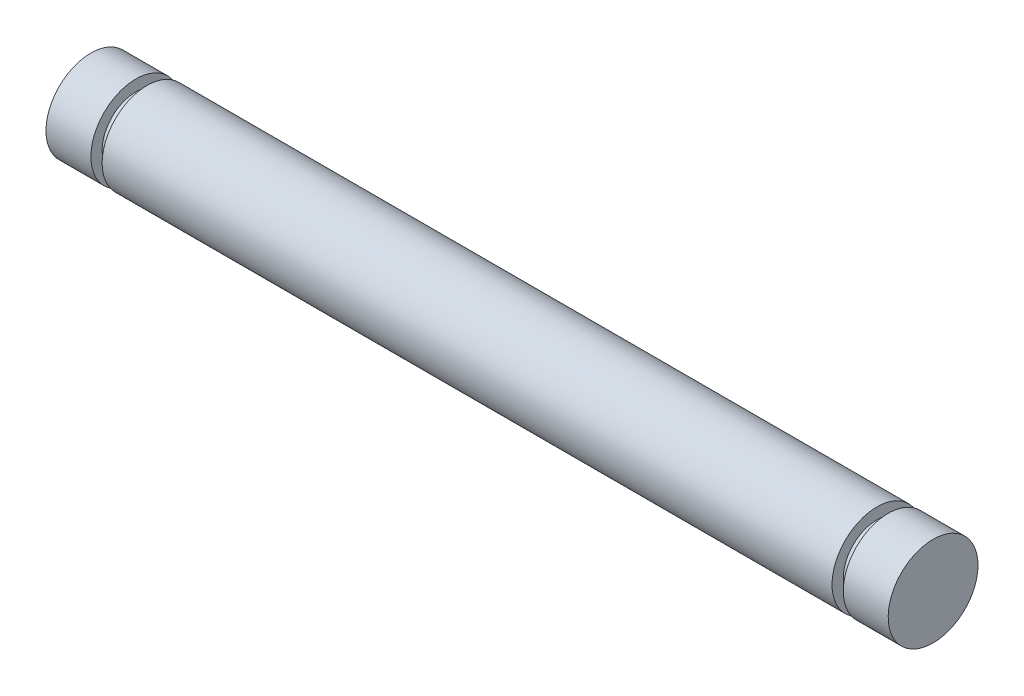
SolidWorks part; units mm, degrees
ref_plane "Alzado" through (0, 0, 0) normal (0, 0, 1) x (1, 0, 0)
ref_plane "Planta" through (0, 0, 0) normal (0, 1, 0) x (1, 0, 0)
ref_plane "Vista lateral" through (0, 0, 0) normal (1, 0, 0) x (0, 0, -1)
sketch "Croquis1" plane through (0, 0, 0) normal (0, 0, 1) x (1, 0, 0)
  line L0 (-37.5, 0) -> (37.5, 0) construction
  line L1 (-37.5, 0) -> (-37.5, 4)
  line L2 (-37.5, 4) -> (-33.5, 4)
  line L3 (-33.5, 4) -> (-33.5, 3)
  line L4 (-33.5, 3) -> (-32.5, 3)
  line L5 (-32.5, 3) -> (-32.5, 4)
  line L6 (-32.5, 4) -> (32.5, 4)
  line L7 (32.5, 4) -> (32.5, 3)
  line L8 (32.5, 3) -> (33.5, 3)
  line L9 (33.5, 3) -> (33.5, 4)
  line L10 (33.5, 4) -> (37.5, 4)
  line L11 (37.5, 4) -> (37.5, 0)
  line L12 (-37.5, 0) -> (37.5, 0)
  point P2 (0, 0)
  point P12 (0, 4)
  dimension "D1" = 8
  dimension "D2" = 6
  dimension "D3" = 75
  dimension "D4" = 4
  dimension "D5" = 1
revolve "Revolución1" add sketch "Croquis1" angle 360 about L0
